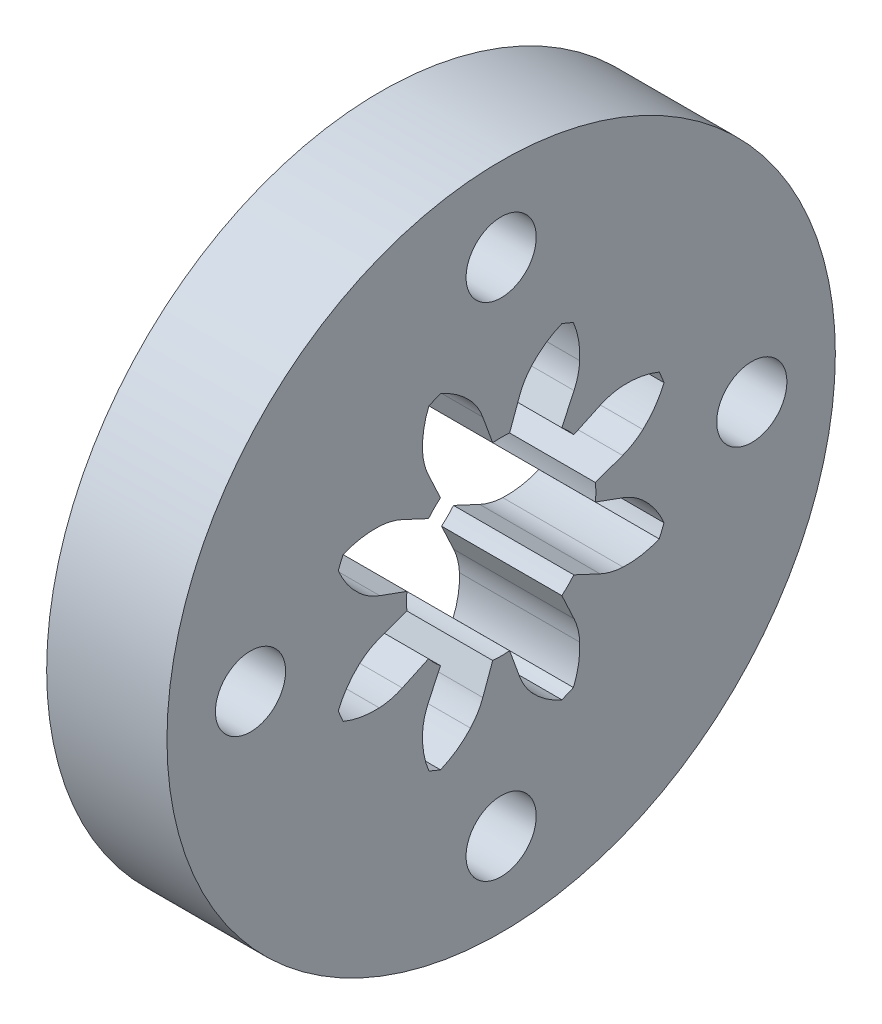
SolidWorks part; units mm, degrees
material "Barra Redonda SAE 1020 - 2\""
ref_plane "Plano frontal" through (0, 0, 0) normal (0, 0, 1) x (1, 0, 0)
ref_plane "Plano superior" through (0, 0, 0) normal (0, 1, 0) x (1, 0, 0)
ref_plane "Plano direito" through (0, 0, 0) normal (1, 0, 0) x (0, 0, -1)
sketch "Esboço1" plane through (0, 0, 0) normal (0, 0, 1) x (1, 0, 0)
  line L0 (-35, 0) -> (35, 0) construction
  line L1 (0, 0) -> (0, 20)
  line L2 (0, 0) -> (7.2, 0)
  line L3 (7.2, 0) -> (7.2, 20)
  line L4 (0, 20) -> (7.2, 20)
  dimension "D1" = 40
  dimension "D3" = 7.2
revolve "Revolução1" add sketch "Esboço1" angle 360 about L0
sketch "Esboço3" plane through (7.2, 0, 0) normal (1, 0, 0) x (0, 0, -1)
  line L0 (0, 0) -> (0, 12.1456) construction
  line L1 (-0.5068, 5.6423) -> (0, 4.25) construction
  line L2 (-0.5068, 5.6423) -> (-1.0979, 7.2665)
  line L3 (0.5068, 5.6423) -> (1.0979, 7.2665)
  line L4 (3.6314, 4.348) -> (4.3619, 5.9145)
  line L5 (4.348, 3.6314) -> (5.9145, 4.3619)
  line L6 (5.6423, 0.5068) -> (7.2665, 1.0979)
  line L7 (5.6423, -0.5068) -> (7.2665, -1.0979)
  line L8 (4.348, -3.6314) -> (5.9145, -4.3619)
  line L9 (3.6314, -4.348) -> (4.3619, -5.9145)
  line L10 (0.5068, -5.6423) -> (1.0979, -7.2665)
  line L11 (-0.5068, -5.6423) -> (-1.0979, -7.2665)
  line L12 (-3.6314, -4.348) -> (-4.3619, -5.9145)
  line L13 (-4.348, -3.6314) -> (-5.9145, -4.3619)
  line L14 (-5.6423, -0.5068) -> (-7.2665, -1.0979)
  line L15 (-5.6423, 0.5068) -> (-7.2665, 1.0979)
  line L16 (-4.348, 3.6314) -> (-5.9145, 4.3619)
  line L17 (-3.6314, 4.348) -> (-4.3619, 5.9145)
  arc A0 (-9.4582, 4.3245) -> (-9.7459, 3.6301) centre (0, 0) ccw construction
  circle A1 centre (0, 0) radius 7.54 construction
  circle A2 centre (0, 0) radius 5.665 construction
  circle A3 centre (0, 0) radius 4.25 construction
  arc A4 (-3.6301, 9.7459) -> (-1.833, 8.4832) centre (-5.5475, 5.1065) cw
  arc A5 (1.833, 8.4832) -> (1.0979, 7.2665) centre (4.556, 6.0079) ccw
  arc A6 (-1.833, 8.4832) -> (-1.0979, 7.2665) centre (-4.556, 6.0079) cw
  arc A7 (3.6301, 9.7459) -> (1.833, 8.4832) centre (5.5475, 5.1065) ccw
  arc A8 (-0.5068, 5.6423) -> (0.5068, 5.6423) centre (0, 0) cw
  arc A9 (4.3245, 9.4582) -> (3.6301, 9.7459) centre (0, 0) ccw construction
  arc A10 (9.7459, 3.6301) -> (9.4582, 4.3245) centre (0, 0) ccw
  arc A11 (4.3245, 9.4582) -> (4.7025, 7.2947) centre (-0.3118, 7.5335) cw
  arc A12 (9.4582, 4.3245) -> (7.2947, 4.7025) centre (7.5335, -0.3118) ccw
  arc A13 (7.2947, 4.7025) -> (5.9145, 4.3619) centre (7.4698, 1.0266) ccw
  arc A14 (4.7025, 7.2947) -> (4.3619, 5.9145) centre (1.0266, 7.4698) cw
  arc A15 (3.6314, 4.348) -> (4.348, 3.6314) centre (0, 0) cw
  arc A16 (9.4582, -4.3245) -> (9.7459, -3.6301) centre (0, 0) ccw
  arc A17 (9.7459, 3.6301) -> (8.4832, 1.833) centre (5.1065, 5.5475) cw
  arc A18 (9.7459, -3.6301) -> (8.4832, -1.833) centre (5.1065, -5.5475) ccw
  arc A19 (8.4832, -1.833) -> (7.2665, -1.0979) centre (6.0079, -4.556) ccw
  arc A20 (8.4832, 1.833) -> (7.2665, 1.0979) centre (6.0079, 4.556) cw
  arc A21 (5.6423, 0.5068) -> (5.6423, -0.5068) centre (0, 0) cw
  arc A22 (3.6301, -9.7459) -> (4.3245, -9.4582) centre (0, 0) ccw
  arc A23 (9.4582, -4.3245) -> (7.2947, -4.7025) centre (7.5335, 0.3118) cw
  arc A24 (4.3245, -9.4582) -> (4.7025, -7.2947) centre (-0.3118, -7.5335) ccw
  arc A25 (4.7025, -7.2947) -> (4.3619, -5.9145) centre (1.0266, -7.4698) ccw
  arc A26 (7.2947, -4.7025) -> (5.9145, -4.3619) centre (7.4698, -1.0266) cw
  arc A27 (4.348, -3.6314) -> (3.6314, -4.348) centre (0, 0) cw
  arc A28 (-4.3245, -9.4582) -> (-3.6301, -9.7459) centre (0, 0) ccw
  arc A29 (3.6301, -9.7459) -> (1.833, -8.4832) centre (5.5475, -5.1065) cw
  arc A30 (-3.6301, -9.7459) -> (-1.833, -8.4832) centre (-5.5475, -5.1065) ccw
  arc A31 (-1.833, -8.4832) -> (-1.0979, -7.2665) centre (-4.556, -6.0079) ccw
  arc A32 (1.833, -8.4832) -> (1.0979, -7.2665) centre (4.556, -6.0079) cw
  arc A33 (0.5068, -5.6423) -> (-0.5068, -5.6423) centre (0, 0) cw
  arc A34 (-9.7459, -3.6301) -> (-9.4582, -4.3245) centre (0, 0) ccw
  arc A35 (-4.3245, -9.4582) -> (-4.7025, -7.2947) centre (0.3118, -7.5335) cw
  arc A36 (-9.4582, -4.3245) -> (-7.2947, -4.7025) centre (-7.5335, 0.3118) ccw
  arc A37 (-7.2947, -4.7025) -> (-5.9145, -4.3619) centre (-7.4698, -1.0266) ccw
  arc A38 (-4.7025, -7.2947) -> (-4.3619, -5.9145) centre (-1.0266, -7.4698) cw
  arc A39 (-3.6314, -4.348) -> (-4.348, -3.6314) centre (0, 0) cw
  arc A41 (-9.7459, -3.6301) -> (-8.4832, -1.833) centre (-5.1065, -5.5475) cw
  arc A42 (-9.7459, 3.6301) -> (-8.4832, 1.833) centre (-5.1065, 5.5475) ccw
  arc A43 (-8.4832, 1.833) -> (-7.2665, 1.0979) centre (-6.0079, 4.556) ccw
  arc A44 (-8.4832, -1.833) -> (-7.2665, -1.0979) centre (-6.0079, -4.556) cw
  arc A45 (-5.6423, -0.5068) -> (-5.6423, 0.5068) centre (0, 0) cw
  arc A46 (-3.6301, 9.7459) -> (-4.3245, 9.4582) centre (0, 0) ccw construction
  arc A47 (-9.4582, 4.3245) -> (-7.2947, 4.7025) centre (-7.5335, -0.3118) cw
  arc A48 (-4.3245, 9.4582) -> (-4.7025, 7.2947) centre (0.3118, 7.5335) ccw
  arc A49 (-4.7025, 7.2947) -> (-4.3619, 5.9145) centre (-1.0266, 7.4698) ccw
  arc A50 (-7.2947, 4.7025) -> (-5.9145, 4.3619) centre (-7.4698, 1.0266) cw
  arc A51 (-4.348, 3.6314) -> (-3.6314, 4.348) centre (0, 0) cw
  arc A52 (-9.4582, 4.3245) -> (-9.7459, 3.6301) centre (0, 0) ccw
  arc A54 (-3.6301, 9.7459) -> (-4.3245, 9.4582) centre (0, 0) ccw
  arc A55 (4.3245, 9.4582) -> (3.6301, 9.7459) centre (0, 0) ccw
  arc A56 (9.7459, 3.6301) -> (9.4582, 4.3245) centre (0, 0) ccw construction
  arc A57 (9.4582, -4.3245) -> (9.7459, -3.6301) centre (0, 0) ccw construction
  arc A58 (3.6301, -9.7459) -> (4.3245, -9.4582) centre (0, 0) ccw construction
  arc A59 (-4.3245, -9.4582) -> (-3.6301, -9.7459) centre (0, 0) ccw construction
  arc A60 (-9.7459, -3.6301) -> (-9.4582, -4.3245) centre (0, 0) ccw construction
  point P110 (0, 0)
  dimension "D1" = 20.8
  dimension "D2" = 15.08
  dimension "D3" = 11.33
  dimension "D4" = 8.5
  dimension "D6" = 5.02
  dimension "D7" = 3.68
  dimension "D5" = 20
  dimension "D8" = 8
extrude "Corte-extrusão2" cut sketch "Esboço3" against normal through all
hole_wizard "Furo roscado de M51" positions "Esboço6" profile "Esboço5" tap size "M5" standard "ISO" end condition up to next
sketch "Esboço6" plane through (7.2, 0, 0) normal (1, 0, 0) x (0, 0, -1)
  point P0 (0, 15)
  point P2 (15, 0)
  point P4 (0, -15)
  point P6 (-15, 0)
  dimension "D1" = 15
  dimension "D2" = 15
  dimension "D3" = 15
  dimension "D4" = 15
sketch "Esboço5" plane through (7.2, 15, 0) normal (0, 1, 0) x (0, 0, -1)
  line L0 (0, 0) -> (0, 7.2)
  line L1 (0, 7.2) -> (2.1, 7.2)
  line L2 (2.1, 7.2) -> (2.1, 0)
  line L5 (2.1, 0) -> (0, 0)
  line L11 (0, -6.35) -> (0, 107.95) construction
  dimension "Thru Tap Drill Dia." = 4.2
  dimension "Thru Tap Drill Depth" = 7.2
cosmetic thread "Rosca de furo1" parameters "D2"=5
cosmetic thread "Rosca de furo2" parameters "D2"=5
cosmetic thread "Rosca de furo3" parameters "D2"=5
cosmetic thread "Rosca de furo4" parameters "D2"=5
